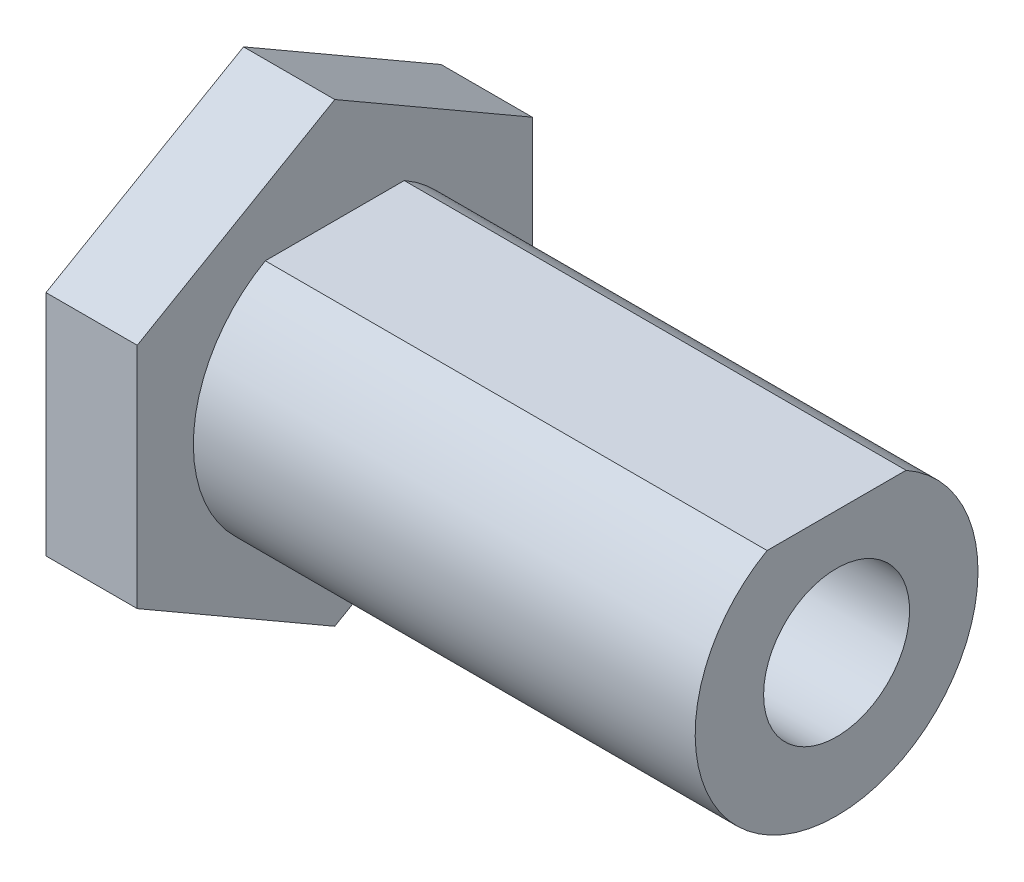
SolidWorks part; units mm, degrees
ref_plane "Front" through (0, 0, 0) normal (0, 0, 1) x (1, 0, 0)
ref_plane "Top" through (0, 0, 0) normal (0, 1, 0) x (1, 0, 0)
ref_plane "Right" through (0, 0, 0) normal (1, 0, 0) x (0, 0, -1)
sketch "Sketch1" plane through (0, 0, 0) normal (0, 0, 1) x (1, 0, 0)
  line L0 (0, 0) -> (13, 0) construction
  line L1 (0, 0) -> (0, 5)
  line L2 (0, 5) -> (2, 5)
  line L3 (2, 5) -> (2, 3.1)
  line L4 (2, 3.1) -> (13, 3.1)
  line L5 (13, 3.1) -> (13, 0)
  line L6 (13, 0) -> (0, 0)
  dimension "D1" = 13
  dimension "D2" = 5
  dimension "D3" = 2
  dimension "D4" = 3.1
revolve "Revolve1" add sketch "Sketch1" angle 360 about L0
sketch "Sketch2" plane through (0, 0, 0) normal (-1, 0, 0) x (0, 0, 1)
  line L1 (0, -5) -> (4.3301, -2.5)
  line L2 (4.3301, -2.5) -> (4.3301, 2.5)
  line L3 (4.3301, 2.5) -> (0, 5)
  line L4 (0, 5) -> (-4.3301, 2.5)
  line L5 (-4.3301, 2.5) -> (-4.3301, -2.5)
  line L6 (-4.3301, -2.5) -> (0, -5)
  circle A0 centre (0, 0) radius 4.3301 construction
extrude "Cut-Extrude1" cut sketch "Sketch2" against normal blind 10 flip side to cut
shell "Shell1" thickness 1.5
sketch "Sketch3" plane through (13, 0, 0) normal (1, 0, 0) x (0, 0, -1)
  line L0 (1.5232, 2.7) -> (-1.5232, 2.7)
  line L1 (0, 2.7) -> (0, -3.1) construction
  circle A0 centre (0, 0) radius 3.1 construction
  arc A1 (1.5232, 2.7) -> (-1.5232, 2.7) centre (0, 0) ccw
  dimension "D1" = 5.8
extrude "Cut-Extrude2" cut sketch "Sketch3" against normal up to surface (11 mm away) up to face at (2, 0, 3.1)
